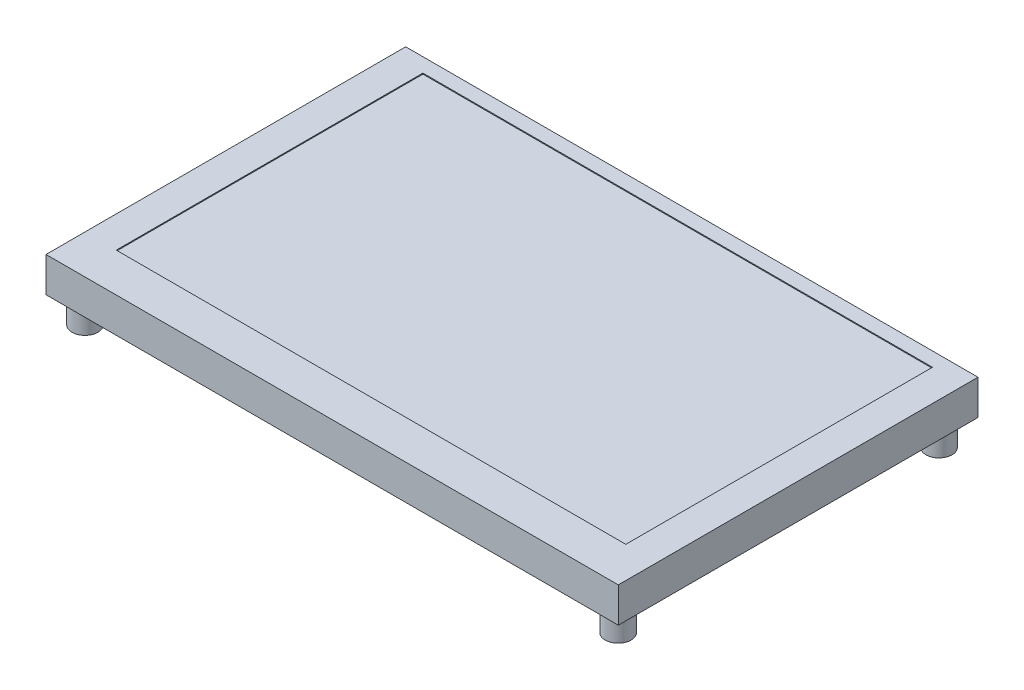
SolidWorks part; units mm, degrees
ref_plane "Front Plane" through (0, 0, 0) normal (0, 0, 1) x (1, 0, 0)
ref_plane "Top Plane" through (0, 0, 0) normal (0, 1, 0) x (1, 0, 0)
ref_plane "Right Plane" through (0, 0, 0) normal (1, 0, 0) x (0, 0, -1)
sketch "Sketch1" plane through (0, 0, 0) normal (0, 1, 0) x (1, 0, 0)
  line L1 (-60.65, -38.12) -> (60.65, -38.12)
  line L2 (-60.65, -38.12) -> (-60.65, 38.12)
  line L3 (-60.65, 38.12) -> (60.65, 38.12)
  line L4 (60.65, -38.12) -> (60.65, 38.12)
  line L5 (-60.65, -38.12) -> (60.65, 38.12) construction
  line L6 (-60.65, 38.12) -> (60.65, -38.12) construction
  point P0 (0, 0)
  dimension "D1" = 121.3
  dimension "D2" = 76.24
extrude "Boss-Extrude1" add sketch "Sketch1" along normal blind 7.4
sketch "Sketch2" plane through (0, 0, 0) normal (0, -1, 0) x (1, 0, 0)
  line L1 (-56.5, -34) -> (56.5, -34) construction
  line L2 (-56.5, -34) -> (-56.5, 34) construction
  line L3 (-56.5, 34) -> (56.5, 34) construction
  line L4 (56.5, -34) -> (56.5, 34) construction
  line L5 (-56.5, -34) -> (56.5, 34) construction
  line L6 (-56.5, 34) -> (56.5, -34) construction
  circle A0 centre (-56.5, 34) radius 2.75
  circle A1 centre (56.5, 34) radius 2.75
  circle A2 centre (56.5, -34) radius 2.75
  circle A3 centre (-56.5, -34) radius 2.75
  circle A4 centre (-56.5, 34) radius 1.5
  circle A5 centre (56.5, 34) radius 1.5
  circle A6 centre (56.5, -34) radius 1.5
  circle A7 centre (-56.5, -34) radius 1.5
  point P0 (0, 0)
  dimension "D3" = 5.5
  dimension "D4" = 3
  dimension "D1" = 113
  dimension "D2" = 68
extrude "Boss-Extrude2" add sketch "Sketch2" along normal blind 5.5
sketch "Sketch3" plane through (0, 0, 0) normal (0, -1, 0) x (1, 0, 0)
  line L0 (60.65, 38.12) -> (60.65, -38.12) construction
  line L1 (-29.35, -24.38) -> (28.65, -24.38) construction
  line L2 (-29.35, -24.38) -> (-29.35, 24.62) construction
  line L3 (-29.35, 24.62) -> (28.65, 24.62) construction
  line L4 (28.65, -24.38) -> (28.65, 24.62) construction
  line L5 (-29.35, -24.38) -> (28.65, 24.62) construction
  line L6 (-29.35, 24.62) -> (28.65, -24.38) construction
  line L7 (-60.65, 38.12) -> (60.65, 38.12) construction
  circle A0 centre (-29.35, 24.62) radius 2.75
  circle A1 centre (-29.35, 24.62) radius 1.5
  circle A2 centre (28.65, 24.62) radius 2.75
  circle A3 centre (28.65, 24.62) radius 1.5
  circle A4 centre (28.65, -24.38) radius 2.75
  circle A5 centre (28.65, -24.38) radius 1.5
  circle A6 centre (-29.35, -24.38) radius 2.75
  circle A7 centre (-29.35, -24.38) radius 1.5
  point P0 (-0.35, 0.12)
  dimension "D3" = 5.5
  dimension "D4" = 3
  dimension "D1" = 58
  dimension "D2" = 49
  dimension "D5" = 32
  dimension "D6" = 13.5
extrude "Boss-Extrude3" add sketch "Sketch3" along normal blind 5.3
sketch "Sketch4" plane through (0, 7.4, 0) normal (0, 1, 0) x (1, 0, 0)
  line L1 (-54, -29.88) -> (54, -29.88)
  line L2 (-54, -29.88) -> (-54, 35.12)
  line L3 (-54, 35.12) -> (54, 35.12)
  line L4 (60.65, -38.12) -> (60.65, 38.12)
  line L5 (60.65, 38.12) -> (-60.65, 38.12)
  line L6 (-60.65, 38.12) -> (-60.65, -38.12)
  line L7 (-60.65, -38.12) -> (60.65, -38.12)
  line L8 (60.65, -38.12) -> (60.65, 38.12)
  line L9 (60.65, 38.12) -> (-60.65, 38.12)
  line L10 (-60.65, 38.12) -> (-60.65, -38.12)
  line L11 (-60.65, -38.12) -> (60.65, -38.12)
  line L12 (54, -29.88) -> (54, 35.12)
  line L13 (-54, -29.88) -> (54, 35.12) construction
  line L14 (-54, 35.12) -> (54, -29.88) construction
  point P2 (0, 2.62)
  dimension "D2" = 108
  dimension "D3" = 65
  dimension "D4" = 3
  dimension "D1" = 0
extrude "Cut-Extrude1" cut sketch "Sketch4" against normal blind 0.2 contours L2 L1 L12 L3
sketch "Sketch5" plane through (0, 0, 0) normal (0, -1, 0) x (-1, 0, 0)
  line L0 (60.65, 38.12) -> (60.65, -38.12) construction
  line L3 (-60.65, 38.12) -> (60.65, 38.12) construction
  circle A0 centre (43.65, 30.12) radius 8
  dimension "D1" = 16
  dimension "D2" = 17
extrude "Boss-Extrude4" add sketch "Sketch5" along normal blind 4
sketch "Sketch6" plane through (0, 0, 0) normal (0, -1, 0) x (1, 0, 0)
  line L0 (-60.65, -38.12) -> (-60.65, 38.12) construction
  line L1 (-47.65, -14.52) -> (-42.65, -14.52)
  line L2 (-47.65, -14.52) -> (-47.65, 7.48)
  line L3 (-47.65, 7.48) -> (-42.65, 7.48)
  line L4 (-42.65, -14.52) -> (-42.65, 7.48)
  line L5 (-47.65, -14.52) -> (-42.65, 7.48) construction
  line L6 (-47.65, 7.48) -> (-42.65, -14.52) construction
  circle A1 centre (-43.65, -30.12) radius 8 construction
  point P0 (-45.15, -3.52)
  dimension "D4" = 15.6
  dimension "D1" = 5
  dimension "D2" = 22
  dimension "D3" = 13
extrude "Boss-Extrude5" add sketch "Sketch6" along normal blind 3
sketch "Sketch8" plane through (0, 7.2, 0) normal (0, 1, 0) x (1, 0, 0)
  line L0 (143.3443, 323.206) -> (948.011, 323.206) construction
sketch "Sketch9" plane through (0, 7.2, 0) normal (0, 1, 0) x (1, 0, 0)
  line L0 (184.7804, -393.6612) -> (1150.1138, -393.6612) construction
